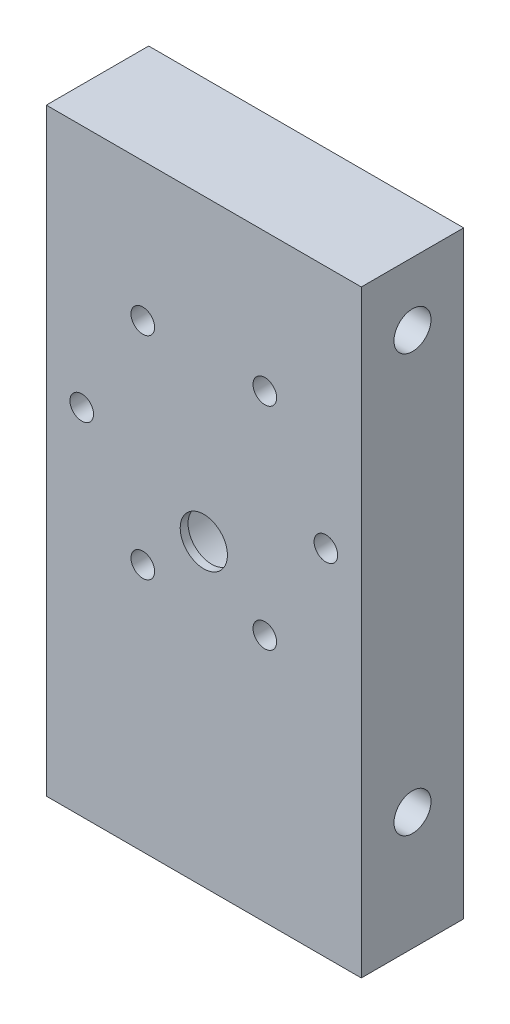
SolidWorks part; units mm, degrees
material "PTEG"
ref_plane "Alzado" through (0, 0, 0) normal (0, 0, 1) x (1, 0, 0)
ref_plane "Planta" through (0, 0, 0) normal (0, 1, 0) x (1, 0, 0)
ref_plane "Vista lateral" through (0, 0, 0) normal (1, 0, 0) x (0, 0, -1)
sketch "Croquis1" plane through (0, 0, 0) normal (0, 0, 1) x (1, 0, 0)
  line L1 (0, 0) -> (40, 0)
  line L2 (0, 0) -> (0, 76)
  line L3 (0, 76) -> (40, 76)
  line L4 (40, 0) -> (40, 76)
  circle A0 centre (20, 38) radius 3
  point P8 (0, 38)
  point P10 (20, 0)
  dimension "D3" = 6
  dimension "D1" = 76
  dimension "D2" = 40
extrude "Saliente-Extruir1" add sketch "Croquis1" along normal blind 13
sketch "Croquis2" plane through (0, 0, 13) normal (0, 0, 1) x (1, 0, 0)
  line L0 (20, 38) -> (20, 45) construction
  circle A0 centre (20, 45) radius 18.5
  dimension "D2" = 37
  dimension "D1" = 7
sketch "Croquis5" plane through (0, 0, 0) normal (0, 0, -1) x (-1, 0, 0)
  circle A0 centre (-20, 45) radius 18.5
  dimension "D1" = 37
extrude "Cortar-Extruir3" cut sketch "Croquis5" against normal blind 6
sketch "Croquis6" plane through (0, 0, 6) normal (0, 0, -1) x (-1, 0, 0)
  line L0 (-20, 45) -> (-35.5, 45) construction
  line L1 (-20, 45) -> (-35.5, 45) construction
  circle A0 centre (-35.5, 45) radius 1.5
  circle A1 centre (-27.75, 58.4234) radius 1.5
  circle A2 centre (-12.25, 58.4234) radius 1.5
  circle A3 centre (-4.5, 45) radius 1.5
  circle A4 centre (-12.25, 31.5766) radius 1.5
  circle A5 centre (-27.75, 31.5766) radius 1.5
  dimension "D2" = 3
  dimension "D4" = 15.5
  dimension "D3" = 6
extrude "Cortar-Extruir4" cut sketch "Croquis6" against normal through all
sketch "Croquis7" plane through (0, 0, 6) normal (0, 0, -1) x (-1, 0, 0)
  circle A0 centre (-20, 38) radius 6
  dimension "D1" = 12
extrude "Cortar-Extruir5" cut sketch "Croquis7" against normal blind 6
sketch "Croquis8" plane through (40, 0, 0) normal (1, 0, 0) x (0, 0, -1)
  line L1 (0, 0) -> (0, 76) construction
  line L4 (-13, 0) -> (0, 0) construction
  line L5 (-13, 76) -> (0, 76) construction
  circle A0 centre (-6.5, 68) radius 2.35
  circle A1 centre (-6.5, 15) radius 2.35
  point P4 (0, 0)
  dimension "D2" = 4.7
  dimension "D1" = 6.5
  dimension "D3" = 15
  dimension "D4" = 8
extrude "Cortar-Extruir6" cut sketch "Croquis8" against normal blind 5
sketch "Croquis9" plane through (0, 0, 0) normal (-1, 0, 0) x (0, 0, 1)
  line L0 (13, 0) -> (0, 0) construction
  line L1 (13, 76) -> (0, 76) construction
  line L2 (13, 76) -> (13, 0) construction
  circle A0 centre (6.5, 68) radius 2.35
  circle A1 centre (6.5, 15) radius 2.35
  point P4 (0, 0)
  dimension "D1" = 15
  dimension "D2" = 4.7
  dimension "D4" = 6.5
  dimension "D3" = 8
extrude "Cortar-Extruir7" cut sketch "Croquis9" against normal blind 5
